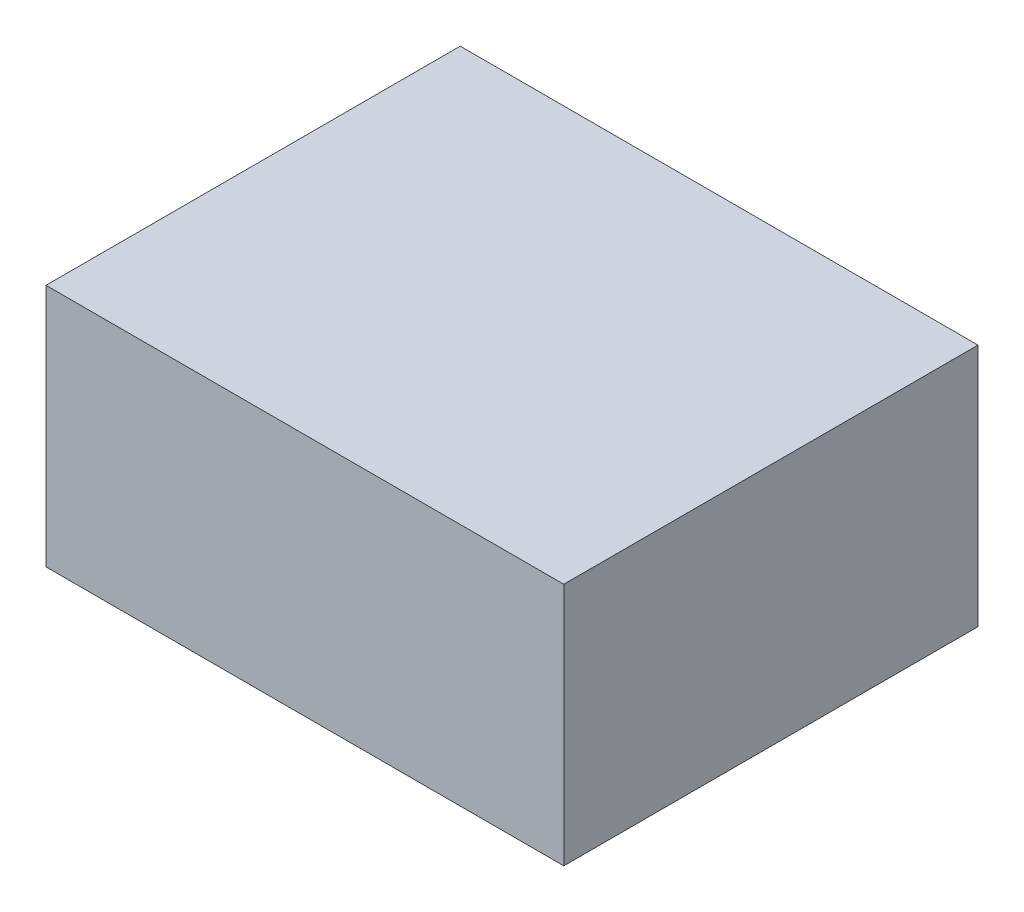
SolidWorks part; units mm, degrees
ref_plane "Front Plane" through (0, 0, 0) normal (0, 0, 1) x (1, 0, 0)
ref_plane "Top Plane" through (0, 0, 0) normal (0, 1, 0) x (1, 0, 0)
ref_plane "Right Plane" through (0, 0, 0) normal (1, 0, 0) x (0, 0, -1)
sketch "Sketch1" plane through (0, 0, 0) normal (0, 1, 0) x (1, 0, 0)
  line L1 (0, 0) -> (1016, 0)
  line L2 (0, 0) -> (0, 812.8)
  line L3 (0, 812.8) -> (1016, 812.8)
  line L4 (1016, 0) -> (1016, 812.8)
  dimension "D1" = 812.8
  dimension "D2" = 1016
extrude "Boss-Extrude1" add sketch "Sketch1" along normal blind 478.536
